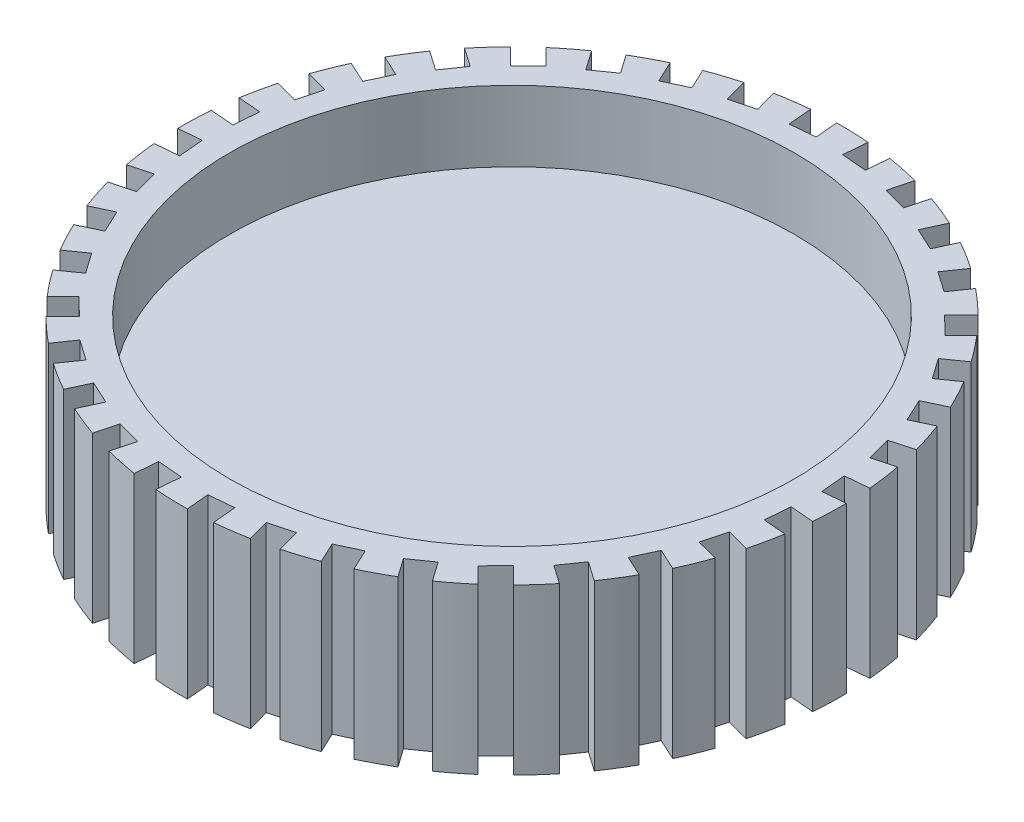
SolidWorks part; units mm, degrees
ref_plane "Front Plane" through (0, 0, 0) normal (0, 0, 1) x (1, 0, 0)
ref_plane "Top Plane" through (0, 0, 0) normal (0, 1, 0) x (1, 0, 0)
ref_plane "Right Plane" through (0, 0, 0) normal (1, 0, 0) x (0, 0, -1)
other "Configuration Table"
sketch "草图1" plane through (0, 0, 0) normal (0, 1, 0) x (1, 0, 0)
  circle A0 centre (0, 0) radius 13
  dimension "D1" = 26
extrude "凸台-拉伸1" add sketch "草图1" along normal blind 7
sketch "草图6" plane through (0, 7, 0) normal (0, 1, 0) x (1, 0, 0)
  circle A0 centre (0, 0) radius 14
  dimension "D1" = 28
extrude "凸台-拉伸4" add sketch "草图6" against normal through all
sketch "草图2" plane through (0, 7, 0) normal (0, 1, 0) x (1, 0, 0)
  circle A0 centre (0, 0) radius 12
  dimension "D1" = 24
extrude "切除-拉伸1" cut sketch "草图2" against normal blind 3
sketch "草图7" plane through (0, 7, 0) normal (0, 1, 0) x (1, 0, 0)
  line L0 (-15.6468, 4.1422) -> (-12.5671, 3.3269)
  line L1 (-15.6468, 4.1422) -> (-15.3762, 5.1646)
  line L2 (-12.5671, 3.3269) -> (-12.2964, 4.3493)
  line L3 (-15.3762, 5.1646) -> (-12.2964, 4.3493)
  line L4 (-14.6898, 6.7963) -> (-11.7985, 5.4586)
  line L5 (-14.6898, 6.7963) -> (-14.2457, 7.7562)
  line L6 (-14.2457, 7.7562) -> (-11.3544, 6.4185)
  line L7 (-11.7985, 5.4586) -> (-11.3544, 6.4185)
  line L8 (-13.2865, 9.2439) -> (-10.6713, 7.4245)
  line L9 (-13.2865, 9.2439) -> (-12.6825, 10.1121)
  line L10 (-12.6825, 10.1121) -> (-10.0673, 8.2926)
  line L11 (-10.6713, 7.4245) -> (-10.0673, 8.2926)
  line L12 (-11.4794, 11.4107) -> (-9.22, 9.1647)
  line L13 (-11.4794, 11.4107) -> (-10.7338, 12.1608)
  line L14 (-10.7338, 12.1608) -> (-8.4744, 9.9148)
  line L15 (-9.22, 9.1647) -> (-8.4744, 9.9148)
  line L16 (-9.3236, 13.2307) -> (-7.4884, 10.6265)
  line L17 (-9.3236, 13.2307) -> (-8.4591, 13.8399)
  line L18 (-8.4591, 13.8399) -> (-6.6239, 11.2358)
  line L19 (-7.4884, 10.6265) -> (-6.6239, 11.2358)
  line L20 (-6.8845, 14.6487) -> (-5.5294, 11.7654)
  line L21 (-6.8845, 14.6487) -> (-5.9273, 15.0986)
  line L22 (-5.9273, 15.0986) -> (-4.5722, 12.2153)
  line L23 (-5.5294, 11.7654) -> (-4.5722, 12.2153)
  line L24 (-4.2361, 15.6217) -> (-3.4024, 12.5469)
  line L25 (-4.2361, 15.6217) -> (-3.2154, 15.8985)
  line L26 (-3.2154, 15.8985) -> (-2.3816, 12.8237)
  line L27 (-3.4024, 12.5469) -> (-2.3816, 12.8237)
  line L28 (-1.4591, 16.1199) -> (-1.1719, 12.9471)
  line L29 (-1.4591, 16.1199) -> (-0.4058, 16.2153)
  line L30 (-0.4058, 16.2153) -> (-0.1186, 13.0424)
  line L31 (-1.1719, 12.9471) -> (-0.1186, 13.0424)
  line L32 (1.3622, 16.1284) -> (1.0941, 12.9539)
  line L33 (1.3622, 16.1284) -> (2.4161, 16.0394)
  line L34 (2.4161, 16.0394) -> (2.148, 12.8649)
  line L35 (1.0941, 12.9539) -> (2.148, 12.8649)
  line L36 (4.1422, 15.6468) -> (3.3269, 12.5671)
  line L37 (4.1422, 15.6468) -> (5.1646, 15.3762)
  line L38 (5.1646, 15.3762) -> (4.3493, 12.2964)
  line L39 (3.3269, 12.5671) -> (4.3493, 12.2964)
  line L40 (6.7963, 14.6898) -> (5.4586, 11.7985)
  line L41 (6.7963, 14.6898) -> (7.7562, 14.2457)
  line L42 (7.7562, 14.2457) -> (6.4185, 11.3544)
  line L43 (5.4586, 11.7985) -> (6.4185, 11.3544)
  line L44 (9.2439, 13.2865) -> (7.4245, 10.6713)
  line L45 (9.2439, 13.2865) -> (10.1121, 12.6825)
  line L46 (10.1121, 12.6825) -> (8.2926, 10.0673)
  line L47 (7.4245, 10.6713) -> (8.2926, 10.0673)
  line L48 (11.4107, 11.4794) -> (9.1647, 9.22)
  line L49 (11.4107, 11.4794) -> (12.1608, 10.7338)
  line L50 (12.1608, 10.7338) -> (9.9148, 8.4744)
  line L51 (9.1647, 9.22) -> (9.9148, 8.4744)
  line L52 (13.2307, 9.3236) -> (10.6265, 7.4884)
  line L53 (13.2307, 9.3236) -> (13.8399, 8.4591)
  line L54 (13.8399, 8.4591) -> (11.2358, 6.6239)
  line L55 (10.6265, 7.4884) -> (11.2358, 6.6239)
  line L56 (14.6487, 6.8845) -> (11.7654, 5.5294)
  line L57 (14.6487, 6.8845) -> (15.0986, 5.9273)
  line L58 (15.0986, 5.9273) -> (12.2153, 4.5722)
  line L59 (11.7654, 5.5294) -> (12.2153, 4.5722)
  line L60 (15.6217, 4.2361) -> (12.5469, 3.4024)
  line L61 (15.6217, 4.2361) -> (15.8985, 3.2154)
  line L62 (15.8985, 3.2154) -> (12.8237, 2.3816)
  line L63 (12.5469, 3.4024) -> (12.8237, 2.3816)
  line L64 (16.1199, 1.4591) -> (12.9471, 1.1719)
  line L65 (16.1199, 1.4591) -> (16.2153, 0.4058)
  line L66 (16.2153, 0.4058) -> (13.0424, 0.1186)
  line L67 (12.9471, 1.1719) -> (13.0424, 0.1186)
  line L68 (16.1284, -1.3622) -> (12.9539, -1.0941)
  line L69 (16.1284, -1.3622) -> (16.0394, -2.4161)
  line L70 (16.0394, -2.4161) -> (12.8649, -2.148)
  line L71 (12.9539, -1.0941) -> (12.8649, -2.148)
  line L72 (15.6468, -4.1422) -> (12.5671, -3.3269)
  line L73 (15.6468, -4.1422) -> (15.3762, -5.1646)
  line L74 (15.3762, -5.1646) -> (12.2964, -4.3493)
  line L75 (12.5671, -3.3269) -> (12.2964, -4.3493)
  line L76 (14.6898, -6.7963) -> (11.7985, -5.4586)
  line L77 (14.6898, -6.7963) -> (14.2457, -7.7562)
  line L78 (14.2457, -7.7562) -> (11.3544, -6.4185)
  line L79 (11.7985, -5.4586) -> (11.3544, -6.4185)
  line L80 (13.2865, -9.2439) -> (10.6713, -7.4245)
  line L81 (13.2865, -9.2439) -> (12.6825, -10.1121)
  line L82 (12.6825, -10.1121) -> (10.0673, -8.2926)
  line L83 (10.6713, -7.4245) -> (10.0673, -8.2926)
  line L84 (11.4794, -11.4107) -> (9.22, -9.1647)
  line L85 (11.4794, -11.4107) -> (10.7338, -12.1608)
  line L86 (10.7338, -12.1608) -> (8.4744, -9.9148)
  line L87 (9.22, -9.1647) -> (8.4744, -9.9148)
  line L88 (9.3236, -13.2307) -> (7.4884, -10.6265)
  line L89 (9.3236, -13.2307) -> (8.4591, -13.8399)
  line L90 (8.4591, -13.8399) -> (6.6239, -11.2358)
  line L91 (7.4884, -10.6265) -> (6.6239, -11.2358)
  line L92 (6.8845, -14.6487) -> (5.5294, -11.7654)
  line L93 (6.8845, -14.6487) -> (5.9273, -15.0986)
  line L94 (5.9273, -15.0986) -> (4.5722, -12.2153)
  line L95 (5.5294, -11.7654) -> (4.5722, -12.2153)
  line L96 (4.2361, -15.6217) -> (3.4024, -12.5469)
  line L97 (4.2361, -15.6217) -> (3.2154, -15.8985)
  line L98 (3.2154, -15.8985) -> (2.3816, -12.8237)
  line L99 (3.4024, -12.5469) -> (2.3816, -12.8237)
  line L100 (1.4591, -16.1199) -> (1.1719, -12.9471)
  line L101 (1.4591, -16.1199) -> (0.4058, -16.2153)
  line L102 (0.4058, -16.2153) -> (0.1186, -13.0424)
  line L103 (1.1719, -12.9471) -> (0.1186, -13.0424)
  line L104 (-1.3622, -16.1284) -> (-1.0941, -12.9539)
  line L105 (-1.3622, -16.1284) -> (-2.4161, -16.0394)
  line L106 (-2.4161, -16.0394) -> (-2.148, -12.8649)
  line L107 (-1.0941, -12.9539) -> (-2.148, -12.8649)
  line L108 (-4.1422, -15.6468) -> (-3.3269, -12.5671)
  line L109 (-4.1422, -15.6468) -> (-5.1646, -15.3762)
  line L110 (-5.1646, -15.3762) -> (-4.3493, -12.2964)
  line L111 (-3.3269, -12.5671) -> (-4.3493, -12.2964)
  line L112 (-6.7963, -14.6898) -> (-5.4586, -11.7985)
  line L113 (-6.7963, -14.6898) -> (-7.7562, -14.2457)
  line L114 (-7.7562, -14.2457) -> (-6.4185, -11.3544)
  line L115 (-5.4586, -11.7985) -> (-6.4185, -11.3544)
  line L116 (-9.2439, -13.2865) -> (-7.4245, -10.6713)
  line L117 (-9.2439, -13.2865) -> (-10.1121, -12.6825)
  line L118 (-10.1121, -12.6825) -> (-8.2926, -10.0673)
  line L119 (-7.4245, -10.6713) -> (-8.2926, -10.0673)
  line L120 (-11.4107, -11.4794) -> (-9.1647, -9.22)
  line L121 (-11.4107, -11.4794) -> (-12.1608, -10.7338)
  line L122 (-12.1608, -10.7338) -> (-9.9148, -8.4744)
  line L123 (-9.1647, -9.22) -> (-9.9148, -8.4744)
  line L124 (-13.2307, -9.3236) -> (-10.6265, -7.4884)
  line L125 (-13.2307, -9.3236) -> (-13.8399, -8.4591)
  line L126 (-13.8399, -8.4591) -> (-11.2358, -6.6239)
  line L127 (-10.6265, -7.4884) -> (-11.2358, -6.6239)
  line L128 (-14.6487, -6.8845) -> (-11.7654, -5.5294)
  line L129 (-14.6487, -6.8845) -> (-15.0986, -5.9273)
  line L130 (-15.0986, -5.9273) -> (-12.2153, -4.5722)
  line L131 (-11.7654, -5.5294) -> (-12.2153, -4.5722)
  line L132 (-15.6217, -4.2361) -> (-12.5469, -3.4024)
  line L133 (-15.6217, -4.2361) -> (-15.8985, -3.2154)
  line L134 (-15.8985, -3.2154) -> (-12.8237, -2.3816)
  line L135 (-12.5469, -3.4024) -> (-12.8237, -2.3816)
  line L136 (-16.1199, -1.4591) -> (-12.9471, -1.1719)
  line L137 (-16.1199, -1.4591) -> (-16.2153, -0.4058)
  line L138 (-16.2153, -0.4058) -> (-13.0424, -0.1186)
  line L139 (-12.9471, -1.1719) -> (-13.0424, -0.1186)
  line L140 (-16.1284, 1.3622) -> (-12.9539, 1.0941)
  line L141 (-16.1284, 1.3622) -> (-16.0394, 2.4161)
  line L142 (-16.0394, 2.4161) -> (-12.8649, 2.148)
  line L143 (-12.9539, 1.0941) -> (-12.8649, 2.148)
  circle A0 centre (0, 0) radius 13 construction
  point P150 (0, 0)
  dimension "D1" = 26
  dimension "D2" = 36
extrude "切除-拉伸2" cut sketch "草图7" against normal through all
